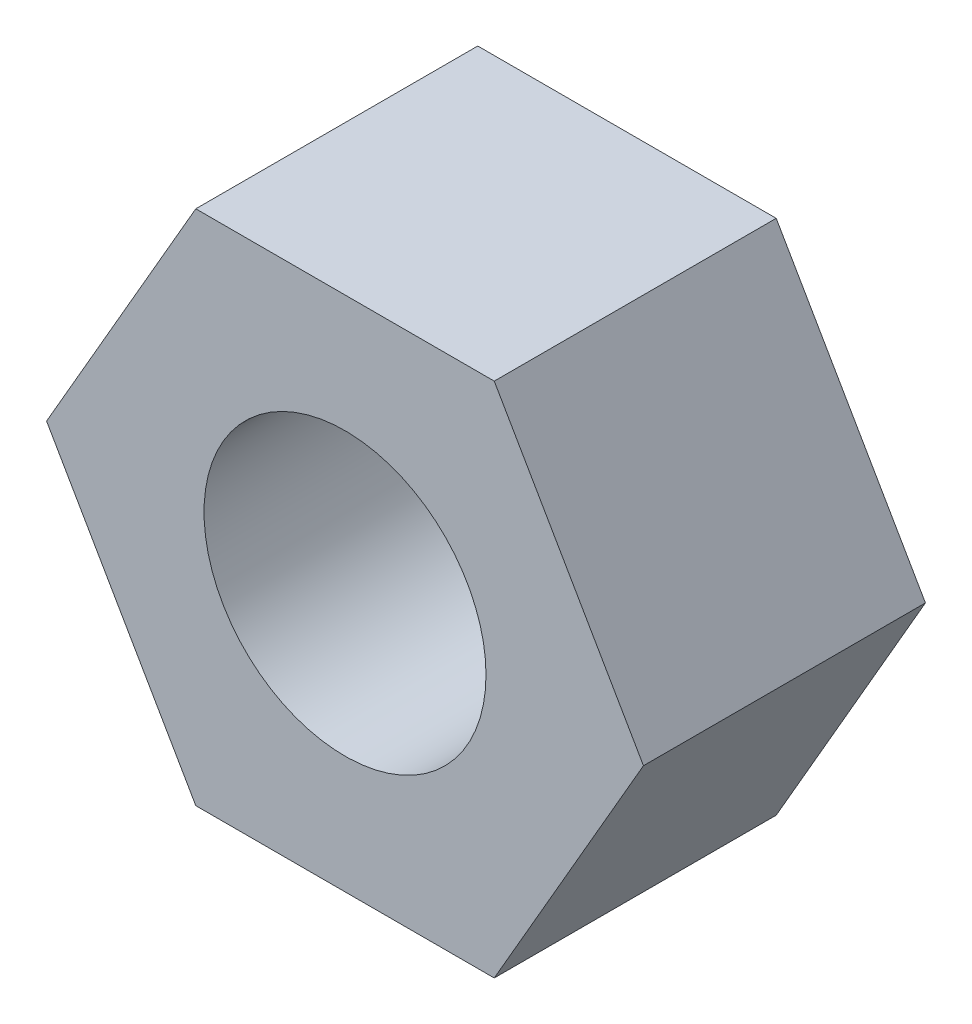
SolidWorks part; units mm, degrees
ref_plane "正面" through (0, 0, 0) normal (0, 0, 1) x (1, 0, 0)
ref_plane "平面" through (0, 0, 0) normal (0, 1, 0) x (1, 0, 0)
ref_plane "右側面" through (0, 0, 0) normal (1, 0, 0) x (0, 0, -1)
sketch "ｽｹｯﾁ2" plane through (0, 0, 0) normal (0, 0, 1) x (1, 0, 0)
  line L1 (3.1754, 0) -> (1.5877, 2.75)
  line L2 (1.5877, 2.75) -> (-1.5877, 2.75)
  line L3 (-1.5877, 2.75) -> (-3.1754, 0)
  line L4 (-3.1754, 0) -> (-1.5877, -2.75)
  line L5 (-1.5877, -2.75) -> (1.5877, -2.75)
  line L6 (1.5877, -2.75) -> (3.1754, 0)
  circle A0 centre (0, 0) radius 2.75 construction
  circle A1 centre (0, 0) radius 1.5
  dimension "D1" = 3
  dimension "D2" = 5.5
extrude "ﾎﾞｽ - 押し出し1" add sketch "ｽｹｯﾁ2" along normal blind 3
